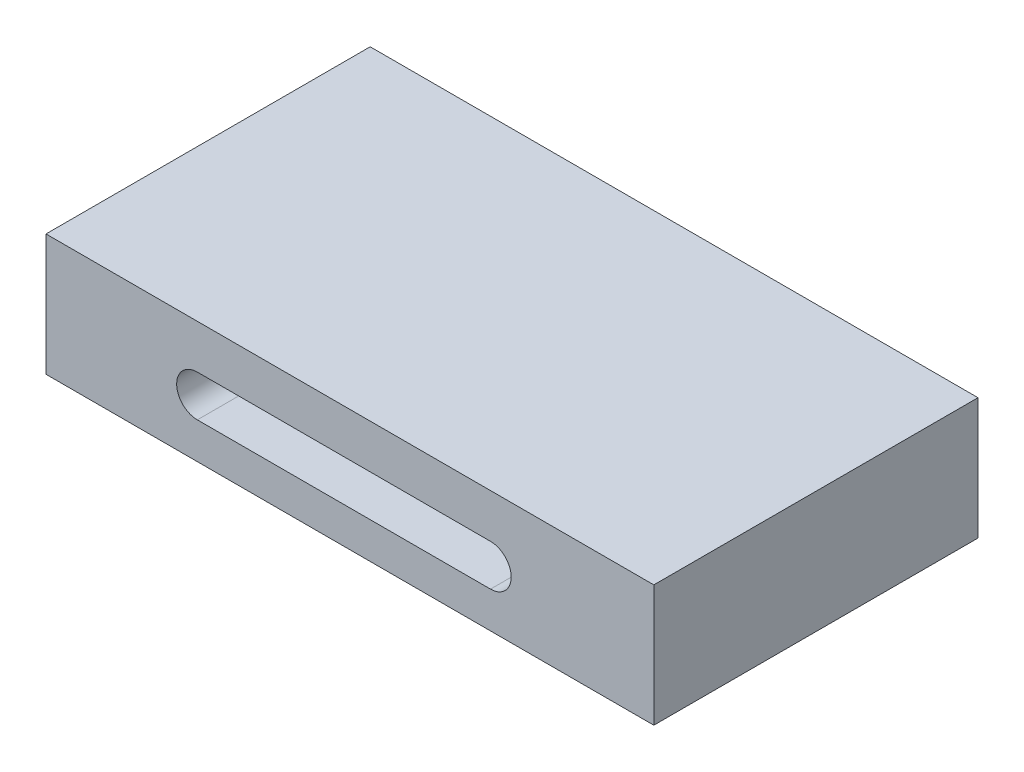
SolidWorks part; units mm, degrees
ref_plane "Front Plane" through (0, 0, 0) normal (0, 0, 1) x (1, 0, 0)
ref_plane "Top Plane" through (0, 0, 0) normal (0, 1, 0) x (1, 0, 0)
ref_plane "Right Plane" through (0, 0, 0) normal (1, 0, 0) x (0, 0, -1)
sketch "Sketch1" plane through (0, 0, 0) normal (0, 1, 0) x (1, 0, 0)
  line L1 (0, 0) -> (-15, 0)
  line L2 (0, 0) -> (0, 8)
  line L3 (0, 8) -> (-15, 8)
  line L4 (-15, 0) -> (-15, 8)
  dimension "D1" = 8
  dimension "D2" = 15
extrude "Boss-Extrude1" add sketch "Sketch1" along normal blind 3
sketch "Sketch19" plane through (0, 0, -8) normal (0, 0, -1) x (-1, 0, 0)
  line L0 (11.2653, 1.4043) -> (4.0303, 1.4043) construction
  line L1 (11.2653, 0.8939) -> (4.0303, 0.8939)
  line L2 (11.2653, 1.9147) -> (4.0303, 1.9147)
  arc A0 (11.2653, 0.8939) -> (11.2653, 1.9147) centre (11.2653, 1.4043) ccw
  arc A1 (4.0303, 1.9147) -> (4.0303, 0.8939) centre (4.0303, 1.4043) ccw
  point P2 (7.6478, 1.4043)
  dimension "D1" = 1.0207
  dimension "D2" = 7.235
extrude "Cut-Extrude2" cut sketch "Sketch19" against normal blind 13
